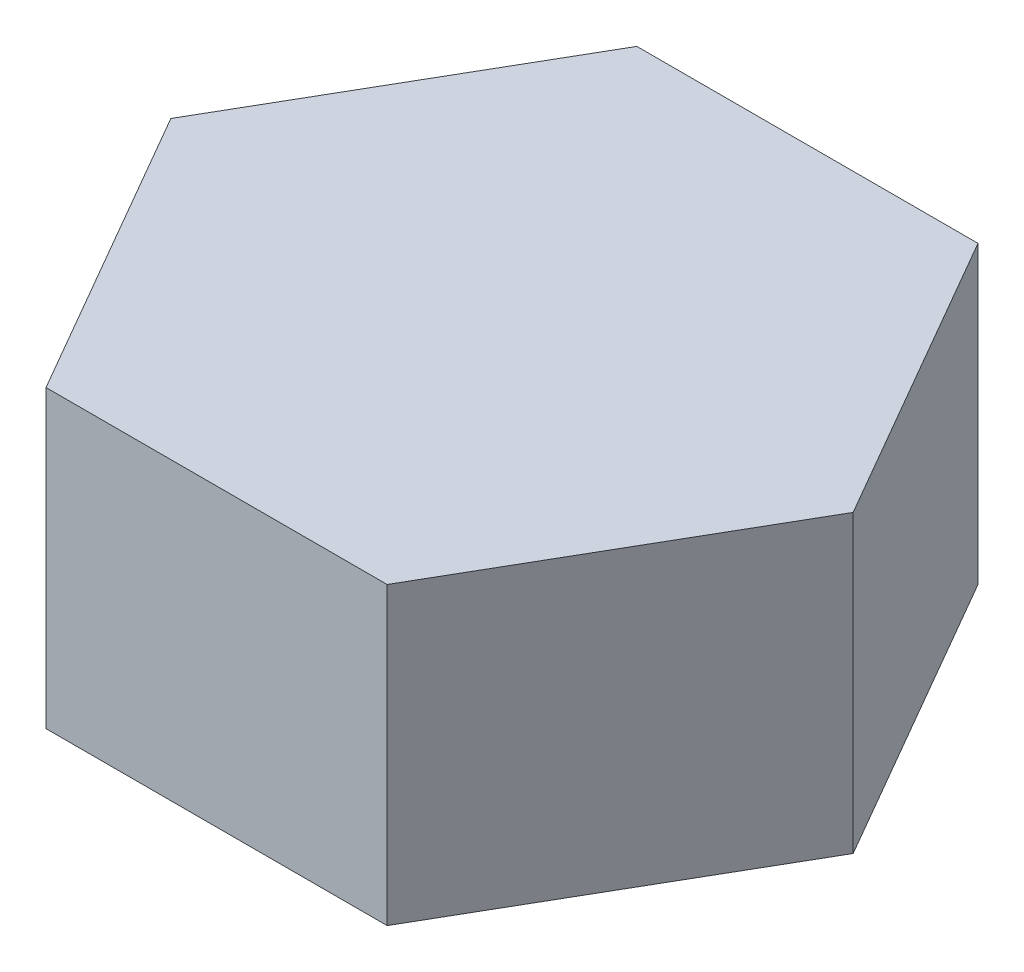
SolidWorks part; units mm, degrees
ref_plane "前视基准面" through (0, 0, 0) normal (0, 0, 1) x (1, 0, 0)
ref_plane "上视基准面" through (0, 0, 0) normal (0, 1, 0) x (1, 0, 0)
ref_plane "右视基准面" through (0, 0, 0) normal (1, 0, 0) x (0, 0, -1)
sketch "草图1" plane through (0, 0, 0) normal (0, 1, 0) x (1, 0, 0)
  line L1 (230.9401, 0) -> (115.4701, 200)
  line L2 (115.4701, 200) -> (-115.4701, 200)
  line L3 (-115.4701, 200) -> (-230.9401, 0)
  line L4 (-230.9401, 0) -> (-115.4701, -200)
  line L5 (-115.4701, -200) -> (115.4701, -200)
  line L6 (115.4701, -200) -> (230.9401, 0)
  circle A0 centre (0, 0) radius 200 construction
  dimension "D1" = 200
extrude "凸台-拉伸1" add sketch "草图1" along normal blind 150 and the other way blind 50
